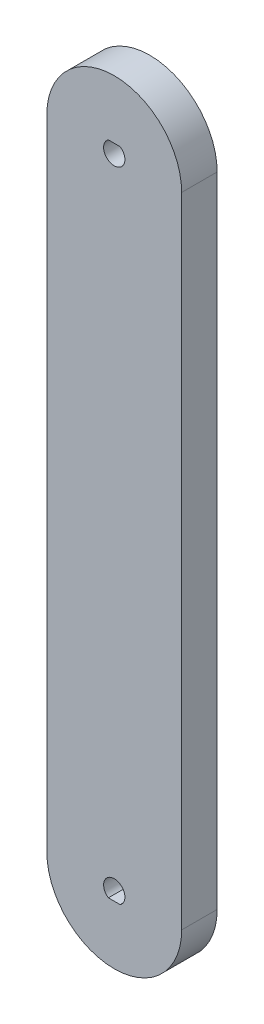
SolidWorks part; units mm, degrees
ref_plane "前视基准面" through (0, 0, 0) normal (0, 0, 1) x (1, 0, 0)
ref_plane "上视基准面" through (0, 0, 0) normal (0, 1, 0) x (1, 0, 0)
ref_plane "右视基准面" through (0, 0, 0) normal (1, 0, 0) x (0, 0, -1)
sketch "草图1" plane through (0, 0, 0) normal (0, 0, 1) x (1, 0, 0)
  line L0 (0, 90) -> (0, -90) construction
  line L1 (19, 90) -> (19, -90)
  line L2 (-19, 90) -> (-19, -90)
  line L3 (-1.6583, 92.5) -> (1.6583, 92.5)
  line L4 (-1.6583, -92.5) -> (1.6583, -92.5)
  arc A0 (19, 90) -> (-19, 90) centre (0, 90) ccw
  arc A1 (-19, -90) -> (19, -90) centre (0, -90) ccw
  circle A2 centre (0, 90) radius 3
  circle A3 centre (0, -90) radius 3
  point P3 (0, 0)
extrude "凸台-拉伸1" add sketch "草图1" along normal blind 10
